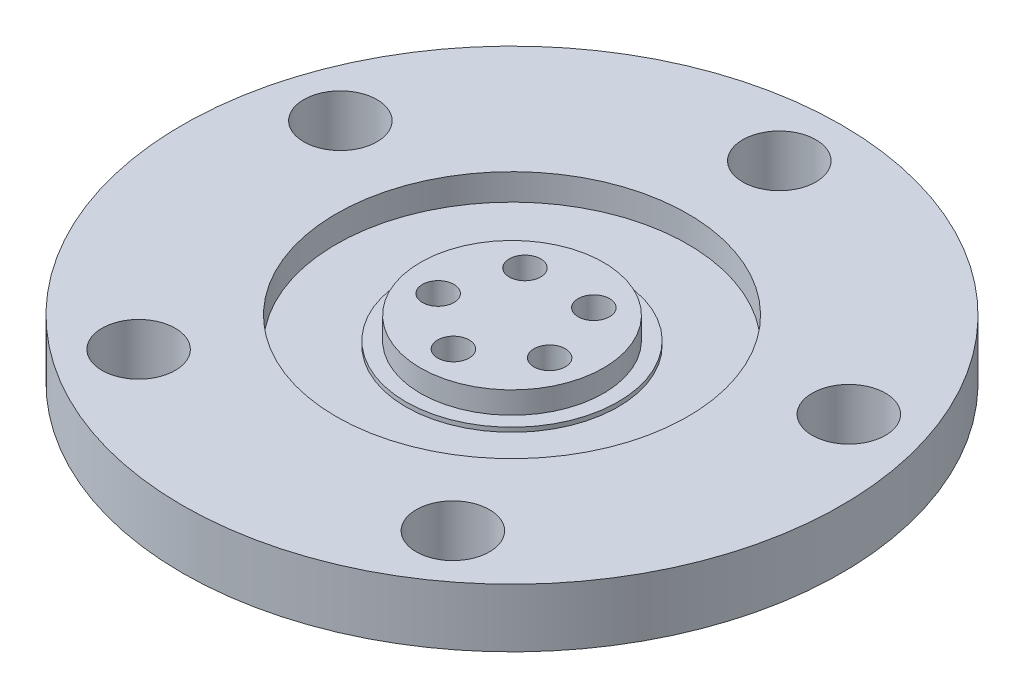
SolidWorks part; units mm, degrees
ref_plane "Front Plane" through (0, 0, 0) normal (0, 0, 1) x (1, 0, 0)
ref_plane "Top Plane" through (0, 0, 0) normal (0, 1, 0) x (1, 0, 0)
ref_plane "Right Plane" through (0, 0, 0) normal (1, 0, 0) x (0, 0, -1)
sketch "Sketch1" plane through (0, 0, 0) normal (0, 1, 0) x (1, 0, 0)
  circle A0 centre (0, 0) radius 36.5 construction
  circle A1 centre (0, 36.5) radius 5
  circle A2 centre (34.7136, 11.2791) radius 5
  circle A3 centre (21.4542, -29.5291) radius 5
  circle A4 centre (-21.4542, -29.5291) radius 5
  circle A5 centre (-34.7136, 11.2791) radius 5
  circle A6 centre (0, 0) radius 45
  point P16 (0, 0)
  dimension "D1" = 73
  dimension "D2" = 10
  dimension "D4" = 90
  dimension "D3" = 5
extrude "Boss-Extrude1" add sketch "Sketch1" along normal blind 8
hole_wizard "Ø4.3 (4.3) Diameter Hole1" positions "Sketch4" profile "Sketch5" hole size "Ø4.3" standard "DIN" end condition through all
sketch "Sketch4" plane through (0, 8, 0) normal (0, 1, 0) x (1, 0, 0)
  line L0 (-34.7136, 11.2791) -> (0, 0) construction
  line L1 (0, 0) -> (0, 36.5) construction
  line L3 (0, 0) -> (-21.4542, 29.5291) construction
  line L5 (0, 36.5) -> (-21.4542, 29.5291) construction
  line L7 (-34.7136, 11.2791) -> (-21.4542, 29.5291) construction
  circle A0 centre (0, 0) radius 8 construction
  point P21 (-4.7023, 6.4721)
  point P27 (4.7023, 6.4721)
  point P28 (7.6085, -2.4721)
  point P29 (0, -8)
  point P30 (-7.6085, -2.4721)
  dimension "D1" = 16
  dimension "D2" = 5
sketch "Sketch5" plane through (-7.6085, 8, 2.4721) normal (1, 0, 0) x (0, 0, 1)
  line L0 (0, 0) -> (0, 8)
  line L1 (0, 8) -> (2.15, 8)
  line L2 (2.15, 8) -> (2.15, 0)
  line L5 (2.15, 0) -> (0, 0)
  line L11 (0, -6.35) -> (0, 107.95) construction
  dimension "Thru Hole Dia." = 4.3
  dimension "Thru Hole Depth" = 8
sketch "Sketch6" plane through (0, 0, 0) normal (0, -1, 0) x (1, 0, 0)
  circle A0 centre (0, 0) radius 19.9
  circle A1 centre (0, 0) radius 30.1
  dimension "D1" = 39.8
  dimension "D2" = 60.2
extrude "Cut-Extrude2" cut sketch "Sketch6" against normal blind 1.5
sketch "Sketch8" plane through (0, 8, 0) normal (0, 1, 0) x (1, 0, 0)
  circle A0 centre (0, 0) radius 12.5
  circle A1 centre (0, 0) radius 24
  dimension "D1" = 25
  dimension "D2" = 48
extrude "Cut-Extrude3" cut sketch "Sketch8" against normal blind 3
sketch "Sketch9" plane through (0, 5, 0) normal (0, 1, 0) x (1, 0, 0)
  circle A0 centre (0, 0) radius 24 construction
  circle A1 centre (0, 0) radius 24 construction
  circle A5 centre (0, 0) radius 14.5
  circle A6 centre (0, 0) radius 24 construction
  circle A7 centre (0, 0) radius 24
extrude "Cut-Extrude4" cut sketch "Sketch9" against normal blind 0.6
